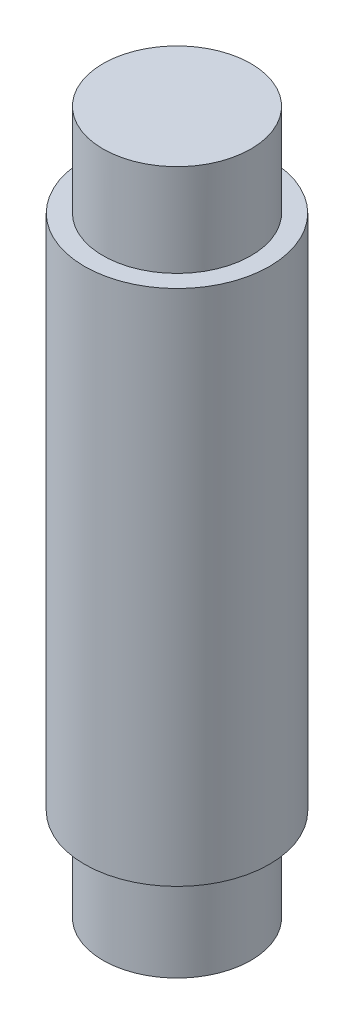
SolidWorks part; units mm, degrees
ref_plane "Front Plane" through (0, 0, 0) normal (0, 0, 1) x (1, 0, 0)
ref_plane "Top Plane" through (0, 0, 0) normal (0, 1, 0) x (1, 0, 0)
ref_plane "Right Plane" through (0, 0, 0) normal (1, 0, 0) x (0, 0, -1)
sketch "Sketch1" plane through (0, 0, 0) normal (0, 0, 1) x (1, 0, 0)
  line L0 (0, 0) -> (0, 14)
revolve "Revolve-Thin1" add sketch "Sketch1" angle 360 about L0 wall 2.5
sketch "Sketch2" plane through (0, 14, 0) normal (0, 1, 0) x (1, 0, 0)
  circle A1 centre (0, 0) radius 2
extrude "Boss-Extrude1" add sketch "Sketch2" along normal blind 2.5
sketch "Sketch3" plane through (0, 0, 0) normal (0, -1, 0) x (-1, 0, 0)
  circle A0 centre (0, 0) radius 2
extrude "Boss-Extrude2" add sketch "Sketch3" along normal blind 2.5
